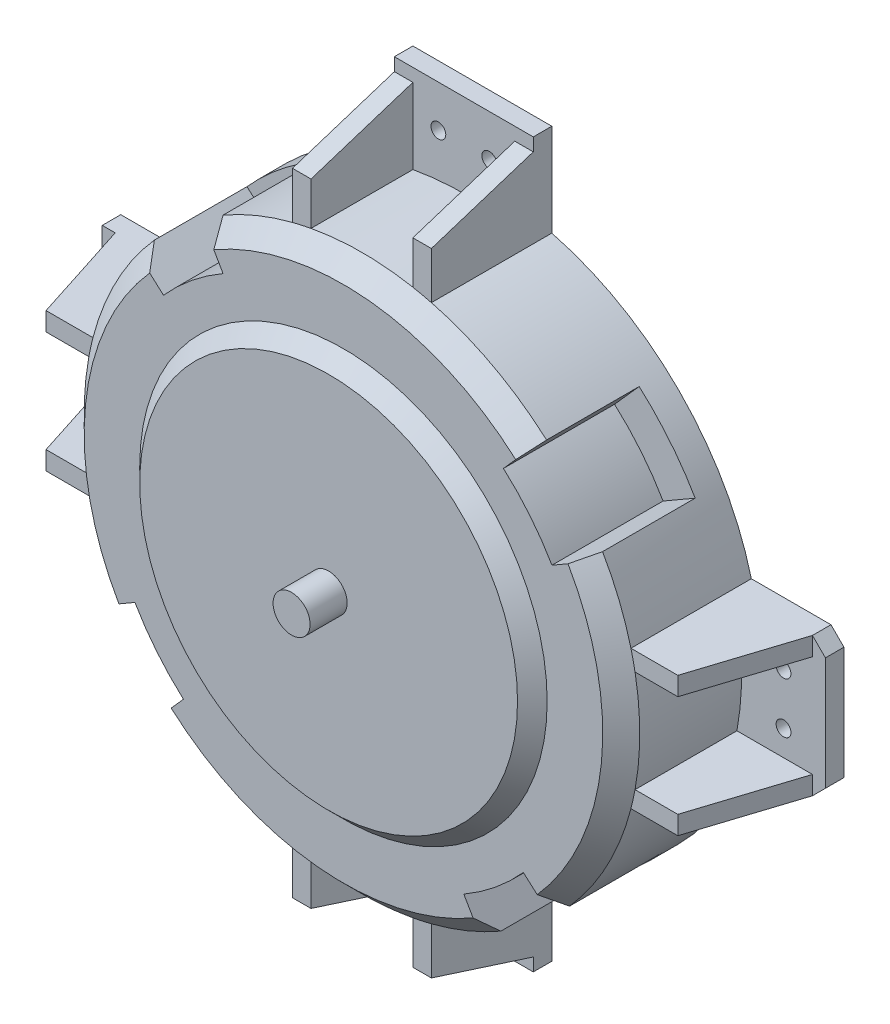
SolidWorks part; units mm, degrees
material "1.7131 (16MnCr5)"
ref_plane "Ön Düzlem" through (0, 0, 0) normal (0, 0, 1) x (1, 0, 0)
ref_plane "Üst Düzlem" through (0, 0, 0) normal (0, 1, 0) x (1, 0, 0)
ref_plane "Sağ Düzlem" through (0, 0, 0) normal (1, 0, 0) x (0, 0, -1)
sketch "Çizim1" plane through (0, 0, 0) normal (0, 0, 1) x (1, 0, 0)
  circle A0 centre (0, 0) radius 150
extrude "Yükseklik-Ekstrüzyon1" add sketch "Çizim1" along normal blind 75
chamfer "Pah1" distance 10 angle 45 1 edges at (150, 0, 75)
sketch "Çizim4" plane through (0, 0, 75) normal (0, 0, 1) x (1, 0, 0)
  line L0 (0, 0) -> (195.2369, 0) construction
  line L1 (195.2369, -37.5) -> (195.2369, 37.5)
  line L2 (195.2369, 37.5) -> (145.2369, 37.5)
  line L3 (195.2369, -37.5) -> (145.2369, -37.5)
  circle A0 centre (0, 0) radius 150 construction
  arc A1 (145.2369, -37.5) -> (145.2369, 37.5) centre (0, 0) ccw
  point P7 (195.2369, 0)
  dimension "D1" = 50
  dimension "D2" = 75
extrude "Yükseklik-Ekstrüzyon2" add sketch "Çizim4" along normal blind 10 from offset 75 offset against normal yes
chamfer "Pah2" distance 7 angle 45 2 edges at (195.2369, -37.5, 5) (195.2369, 37.5, 5)
sketch "Çizim7" plane through (0, 37.5, 0) normal (0, 1, 0) x (1, 0, 0)
  line L0 (145.2369, 0) -> (145.2369, -65.0152)
  line L1 (145.2369, -65.0152) -> (170.5569, -65.0152)
  line L2 (170.5569, -65.0152) -> (188.2369, -10)
  line L3 (188.2369, -10) -> (188.2369, 0)
  line L4 (188.2369, 0) -> (145.2369, 0)
  line L5 (69.154, -65.0086) -> (198.1299, -65.0086) construction
  dimension "D1" = 17.68
extrude "Yükseklik-Ekstrüzyon3" add sketch "Çizim7" against normal blind 10
sketch "Çizim8" plane through (0, 0, 10) normal (0, 0, 1) x (1, 0, 0)
  line L0 (195.2369, 0) -> (150, 0) construction
  line L2 (195.2369, -30.5) -> (195.2369, 30.5) construction
  line L3 (172.6184, 0) -> (172.6184, 27.5) construction
  line L5 (170.5569, 27.5) -> (188.2369, 27.5) construction
  arc A0 (145.2369, 37.5) -> (147.4576, 27.5) centre (0, 0) ccw construction
  circle A1 centre (172.6184, 13.75) radius 4
  dimension "D1" = 8
extrude "Kes-Ekstrüzyon1" cut sketch "Çizim8" against normal through all
ref_plane "Düzlem1" through (0, 0, 0) normal (0, 1, 0) x (1, 0, 0)
mirror "Aynalama1" about plane through (0, 0, 0) normal (0, 1, 0) of "Kes-Ekstrüzyon1", "Yükseklik-Ekstrüzyon3"
pattern_circular "Dairesel Kaplama1" count 4 over 360 about axis through (0, 0, 0) along (0, 0, 1) of "Yükseklik-Ekstrüzyon2", "Yükseklik-Ekstrüzyon3", "Aynalama1", "Kes-Ekstrüzyon1"
sketch "Çizim9" plane through (0, 0, 75) normal (0, 0, 1) x (1, 0, 0)
  line L0 (130, 0) -> (-130, 0) construction
  line L1 (0, 130) -> (0, -130) construction
  line L2 (-112.5833, -65) -> (-129.9038, -75)
  line L3 (-86.3834, -97.1489) -> (-99.6732, -112.0949)
  arc A0 (-129.9038, -75) -> (-99.6732, -112.0949) centre (0, 0) ccw
  circle A2 centre (0, 0) radius 130
  arc A3 (-112.5833, -65) -> (-86.3834, -97.1489) centre (0, 0) ccw
  dimension "D2" = 30
  dimension "D3" = 41.643
  dimension "D1" = 10
extrude "Kes-Ekstrüzyon2" cut sketch "Çizim9" against normal blind 60
pattern_circular "Dairesel Kaplama2" count 4 over 360 about axis through (0, 0, 75) along (0, 0, 1) of "Kes-Ekstrüzyon2"
sketch "Çizim10" plane through (0, 0, 75) normal (0, 0, 1) x (1, 0, 0)
  circle A0 centre (0, 0) radius 110
extrude "Yükseklik-Ekstrüzyon4" add sketch "Çizim10" along normal blind 8 draft 45
sketch "Çizim11" plane through (0, 0, 83) normal (0, 0, 1) x (1, 0, 0)
  circle A0 centre (0, 0) radius 10
  dimension "D1" = 20
extrude "Yükseklik-Ekstrüzyon5" add sketch "Çizim11" along normal blind 20
